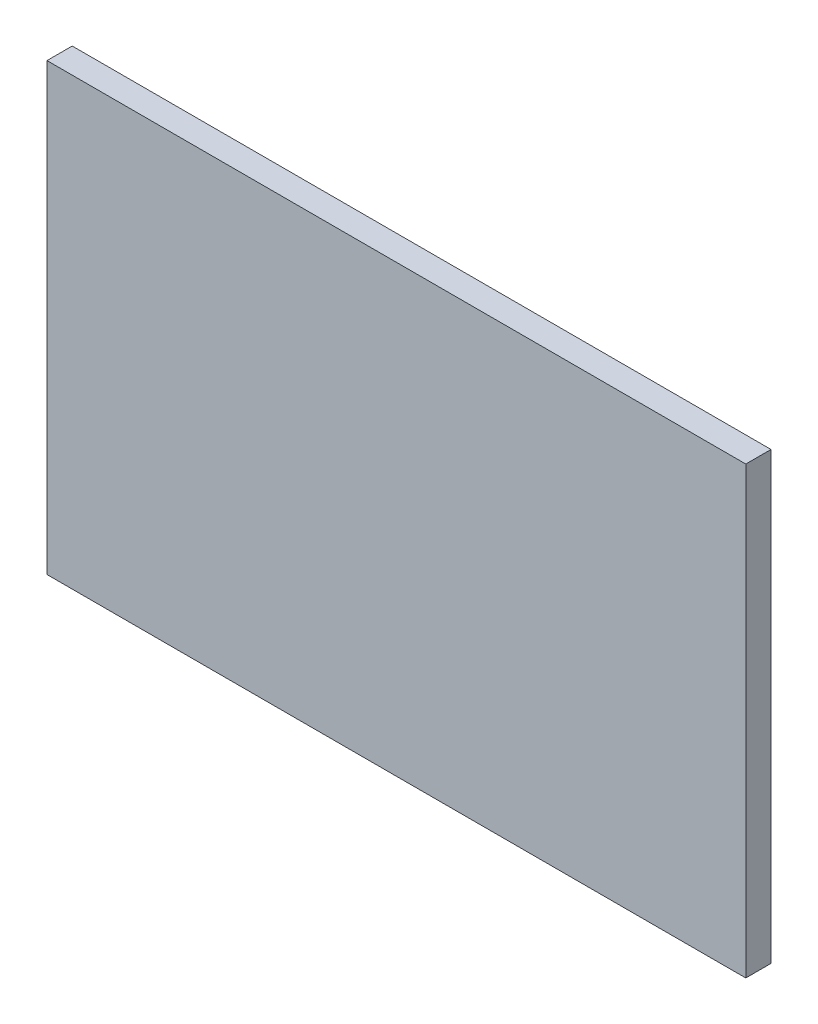
SolidWorks part; units mm, degrees
material "Acrylic (Medium-high impact)"
ref_plane "Front Plane" through (0, 0, 0) normal (0, 0, 1) x (1, 0, 0)
ref_plane "Top Plane" through (0, 0, 0) normal (0, 1, 0) x (1, 0, 0)
ref_plane "Right Plane" through (0, 0, 0) normal (1, 0, 0) x (0, 0, -1)
sketch "Sketch1" plane through (0, 0, 0) normal (0, 0, 1) x (1, 0, 0)
  line L1 (52.7558, -33.6042) -> (-52.7558, -33.6042)
  line L2 (52.7558, -33.6042) -> (52.7558, 33.6042)
  line L3 (52.7558, 33.6042) -> (-52.7558, 33.6042)
  line L4 (-52.7558, -33.6042) -> (-52.7558, 33.6042)
  line L5 (52.7558, -33.6042) -> (-52.7558, 33.6042) construction
  line L6 (52.7558, 33.6042) -> (-52.7558, -33.6042) construction
  point P0 (0, 0)
  dimension "D1" = 67.2084
  dimension "D2" = 105.5116
extrude "Boss-Extrude1" add sketch "Sketch1" along normal blind 3.81
